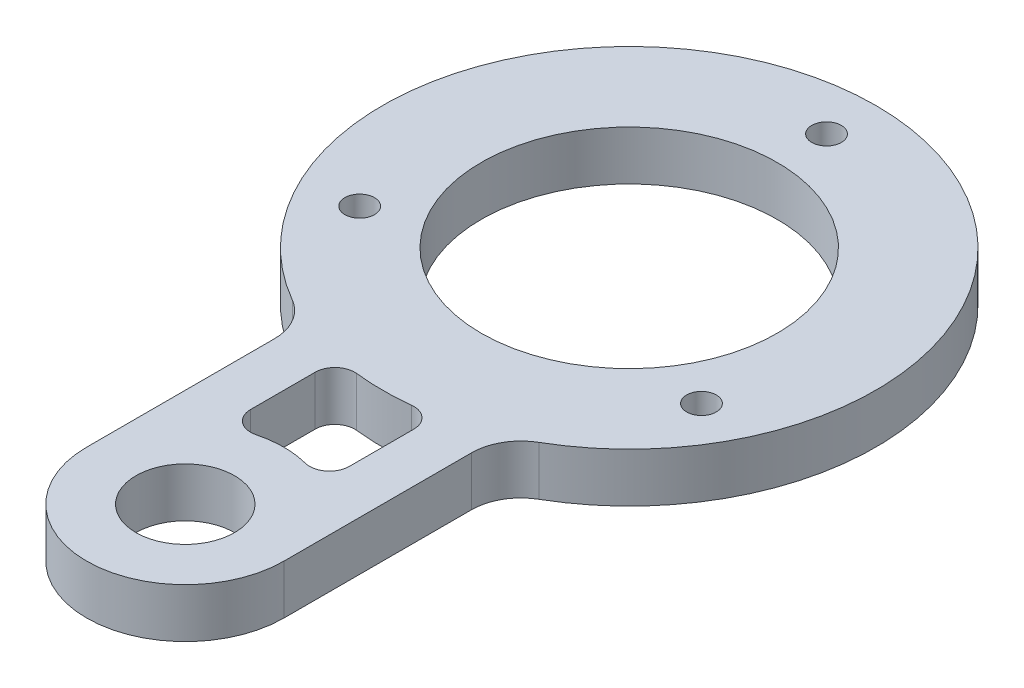
SolidWorks part; units mm, degrees
ref_plane "前视基准面" through (0, 0, 0) normal (0, 0, 1) x (1, 0, 0)
ref_plane "上视基准面" through (0, 0, 0) normal (0, 1, 0) x (1, 0, 0)
ref_plane "右视基准面" through (0, 0, 0) normal (1, 0, 0) x (0, 0, -1)
other "Configuration Table"
sketch "草图1" plane through (0, 0, 0) normal (0, 1, 0) x (1, 0, 0)
  line L0 (0, 0) -> (0, 45) construction
  line L3 (-10, 0) -> (-10, 22.0871)
  line L4 (10, 0) -> (10, 22.0871)
  circle A0 centre (0, 0) radius 5
  arc A1 (-10, 0) -> (10, 0) centre (0, 0) ccw
  circle A2 centre (0, 45) radius 15
  arc A3 (10, 22.0871) -> (-10, 22.0871) centre (0, 45) ccw
  circle A4 centre (0, 45) radius 20 construction
  circle A5 centre (0, 65) radius 1.5
  circle A6 centre (17.3205, 35) radius 1.5
  circle A7 centre (-17.3205, 35) radius 1.5
  dimension "D2" = 20
  dimension "D3" = 25
  dimension "D4" = 10
  dimension "D5" = 30
  dimension "D6" = 40
  dimension "D8" = 3
  dimension "D1" = 45
  dimension "D7" = 3
extrude "凸台-拉伸1" add sketch "草图1" along normal blind 5
sketch "草图2" plane through (0, 5, 0) normal (0, 1, 0) x (1, 0, 0)
  line L2 (-5, 22.0871) -> (-5, 0)
  line L3 (-5, 22.0871) -> (-5, 0)
  line L5 (5, 0) -> (5, 22.0871)
  line L6 (5, 0) -> (5, 22.0871)
  circle A0 centre (0, 45) radius 25
  arc A1 (10, 22.0871) -> (-10, 22.0871) centre (0, 45) ccw construction
  circle A4 centre (0, 0) radius 10
  circle A5 centre (0, 0) radius 10
  dimension "D1" = 5
  dimension "D2" = 5
  dimension "D3" = 5
extrude "切除-拉伸1" cut sketch "草图2" against normal through all contours A5 L6 A0 L3
fillet "圆角1" radius 2 4 edges at (-5, 2.5, -20.5051) (5, 2.5, -20.5051) (5, 2.5, -8.6603) (-5, 2.5, -8.6603)
fillet "圆角2" radius 5 2 edges at (-10, 2.5, -22.0871) (10, 2.5, -22.0871)
